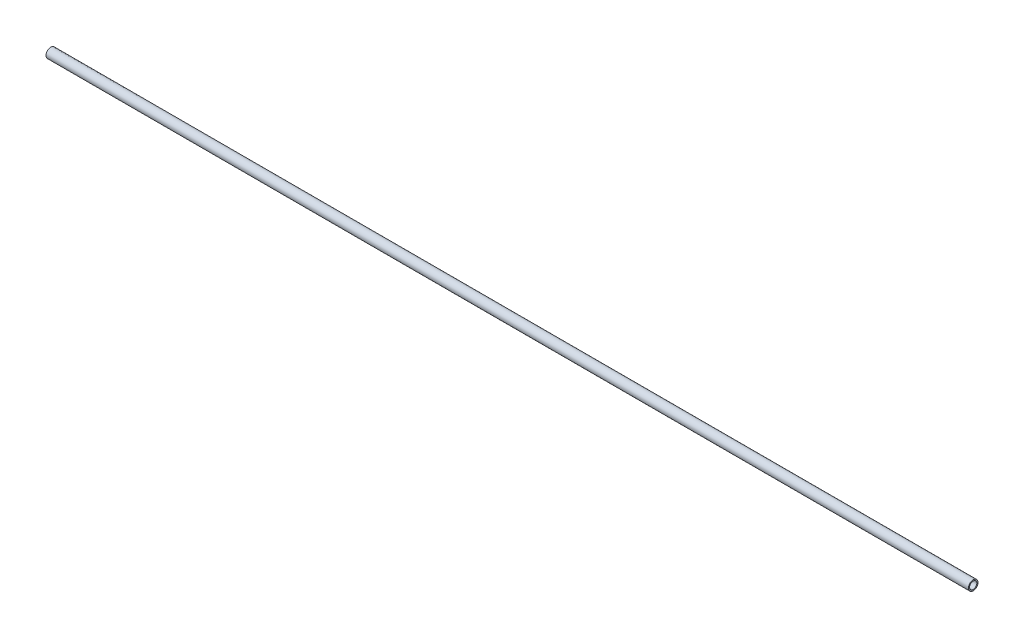
SolidWorks part; units mm, degrees
ref_plane "Front Plane" through (0, 0, 0) normal (0, 0, 1) x (1, 0, 0)
ref_plane "Top Plane" through (0, 0, 0) normal (0, 1, 0) x (1, 0, 0)
ref_plane "Right Plane" through (0, 0, 0) normal (1, 0, 0) x (0, 0, -1)
sketch "Sketch1" plane through (0, 0, 0) normal (1, 0, 0) x (0, 0, -1)
  circle A0 centre (0, 0) radius 9.525
  circle A1 centre (0, 0) radius 7.112
  dimension "D1" = 19.05
  dimension "D2" = 2.413
extrude "Boss-Extrude1" add sketch "Sketch1" along normal blind 1828.8
